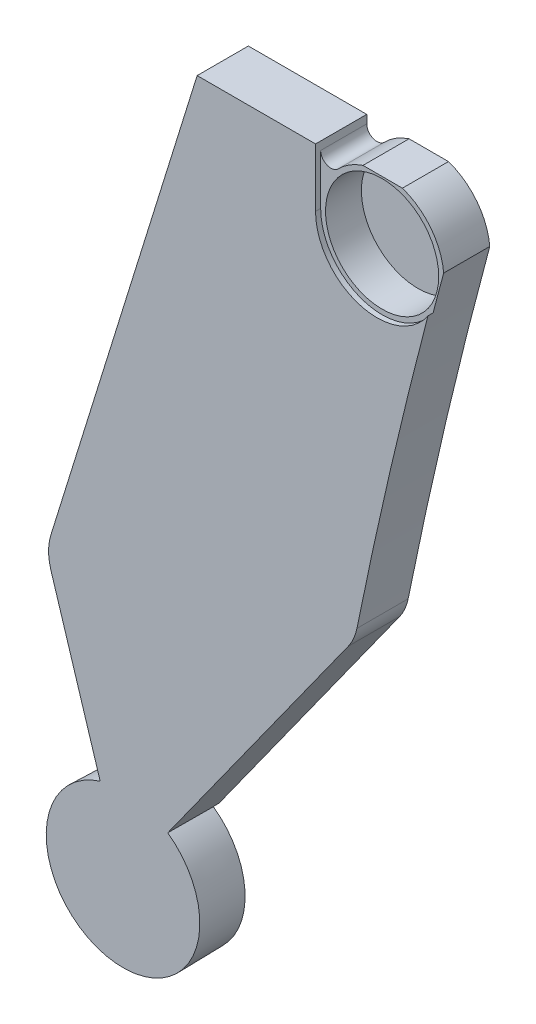
SolidWorks part; units mm, degrees
ref_plane "Front Plane" through (0, 0, 0) normal (0, 0, 1) x (1, 0, 0)
ref_plane "Top Plane" through (0, 0, 0) normal (0, 1, 0) x (1, 0, 0)
ref_plane "Right Plane" through (0, 0, 0) normal (1, 0, 0) x (0, 0, -1)
sketch "Sketch2" plane through (0, 0, 0) normal (0, 0, 1) x (1, 0, 0)
  line L0 (0, 0) -> (70, 0)
  line L1 (110, 290) -> (50, 290)
  arc A0 (70, 0) -> (110, 290) centre (1141.25, 0) cw
  arc A1 (0, 0) -> (50, 290) centre (866, 0) cw
  arc A2 (35, 0) -> (80, 290) centre (929.1503, 9.7439) cw construction
  dimension "D3" = 40
  dimension "D4" = 290
  dimension "D1" = 70
  dimension "D2" = 60
extrude "Boss-Extrude1" add sketch "Sketch2" along normal blind 10
sketch "Sketch6" plane through (0, 0, 10) normal (0, 0, 1) x (1, 0, 0)
  line L0 (110, 290) -> (50, 290) construction
  line L1 (-33.2045, 210) -> (133.7181, 210)
  line L2 (133.7181, 210) -> (133.7181, -43.3471)
  line L3 (133.7181, -43.3471) -> (-33.2045, -43.3471)
  line L4 (-33.2045, -43.3471) -> (-33.2045, 210)
  dimension "D2" = 80
extrude "Cut-Extrude3" cut sketch "Sketch6" against normal up to next
sketch "Sketch8" plane through (0, 0, 10) normal (0, 0, 1) x (1, 0, 0)
  line L0 (25.8476, 210) -> (45.5218, 146.8587)
  line L1 (45.5218, 146.8587) -> (90.7851, 210)
  line L4 (25.8476, 210) -> (90.7851, 210)
  line L5 (110, 290) -> (50, 290)
  line L6 (25.8476, 210) -> (90.7851, 210)
  arc A0 (80, 290) -> (35, 0) centre (929.1503, 9.7439) ccw construction
  arc A3 (50, 290) -> (25.8476, 210) centre (866, 0) ccw
  arc A4 (110, 290) -> (90.7851, 210) centre (1141.25, 0) ccw
  dimension "D1" = 0
extrude "Boss-Extrude2" add sketch "Sketch8" against normal up to surface (10 mm away) up to face at (68.7247, 250.119, 0)
sketch "Sketch11" plane through (0, 0, 10) normal (0, 0, 1) x (1, 0, 0)
  line L0 (45.5218, 146.8587) -> (90.7851, 210) construction
  line L1 (25.8476, 210) -> (45.5218, 146.8587) construction
  circle A1 centre (45.5218, 146.8587) radius 15
  dimension "D1" = 30
extrude "Boss-Extrude4" add sketch "Sketch11" against normal blind 9 draft 1
fillet "Fillet1" radius 10 2 edges at (25.8476, 210, 5) (90.7851, 210, 5)
sketch "Sketch15" plane through (0, 0, 1) normal (0, 0, -1) x (-1, 0, 0)
  circle A0 centre (-45.5218, 146.8587) radius 11.5
  dimension "D1" = 23
extrude "Cut-Extrude6" cut sketch "Sketch15" against normal mid plane 14
sketch "Sketch17" plane through (0, 0, 1) normal (0, 0, -1) x (-1, 0, 0)
  circle A0 centre (-45.5218, 146.8587) radius 15
extrude "Cut-Extrude7" cut sketch "Sketch17" along normal blind 2
sketch "Sketch18" plane through (0, 0, 10) normal (0, 0, 1) x (1, 0, 0)
  line L5 (83.1244, 278.597) -> (83.1244, 292.6631)
  line L6 (83.1244, 292.6631) -> (111.6992, 292.6631)
  line L7 (111.6992, 292.6631) -> (111.6992, 271.9671)
  line L8 (111.6992, 271.9671) -> (105.1266, 271.9671)
  arc A1 (83.1244, 278.597) -> (105.1266, 271.9671) centre (95.1244, 278.597) ccw
  dimension "D1" = 24
extrude "Cut-Extrude8" cut sketch "Sketch18" against normal blind 1
sketch "Sketch19" plane through (0, 0, 9) normal (0, 0, 1) x (1, 0, 0)
  circle A1 centre (95.1244, 278.597) radius 11.05
  dimension "D1" = 22.1
extrude "Cut-Extrude9" cut sketch "Sketch19" against normal blind 7
sketch "Sketch21" plane through (0, 0, 9) normal (0, 0, 1) x (1, 0, 0)
  line L0 (110, 290) -> (83.1244, 290) construction
  line L1 (83.1244, 278.597) -> (83.1244, 291.9615)
  line L2 (83.1244, 291.9615) -> (91.3866, 291.9615)
  line L3 (91.3866, 291.9615) -> (91.3866, 290)
  line L4 (97.4187, 290.4495) -> (97.4187, 291.9615)
  line L5 (97.4187, 291.9615) -> (113.1299, 291.9615)
  line L6 (113.1299, 291.9615) -> (113.1299, 278.597)
  line L7 (113.1299, 278.597) -> (107.197, 278.597)
  arc A0 (83.1244, 278.597) -> (91.3866, 290) centre (95.1244, 278.597) cw
  arc A1 (83.1244, 278.597) -> (105.0799, 271.897) centre (95.1244, 278.597) ccw construction
  arc A2 (83.1244, 278.597) -> (105.0799, 271.897) centre (95.1244, 278.597) ccw construction
  arc A3 (97.4187, 290.4495) -> (107.197, 278.597) centre (95.1244, 278.597) cw
extrude "Cut-Extrude10" cut sketch "Sketch21" against normal blind 10
fillet "Fillet2" radius 2 1 edges at (83.1244, 278.597, 4.5)
sketch "Sketch22" plane through (0, 0, 10) normal (0, 0, 1) x (1, 0, 0)
  line L0 (60, 290) -> (29.3802, 191.412)
  line L1 (83.1244, 290) -> (50, 290) construction
  line L2 (29.3802, 191.412) -> (8.7119, 204.4254)
  line L3 (8.7119, 204.4254) -> (44.6901, 301.6432)
  line L4 (44.6901, 301.6432) -> (60, 290)
  dimension "D1" = 10
extrude "Cut-Extrude11" cut sketch "Sketch22" against normal blind 10
fillet "Fillet3" radius 10 1 edges at (30.508, 195.0432, 5)
